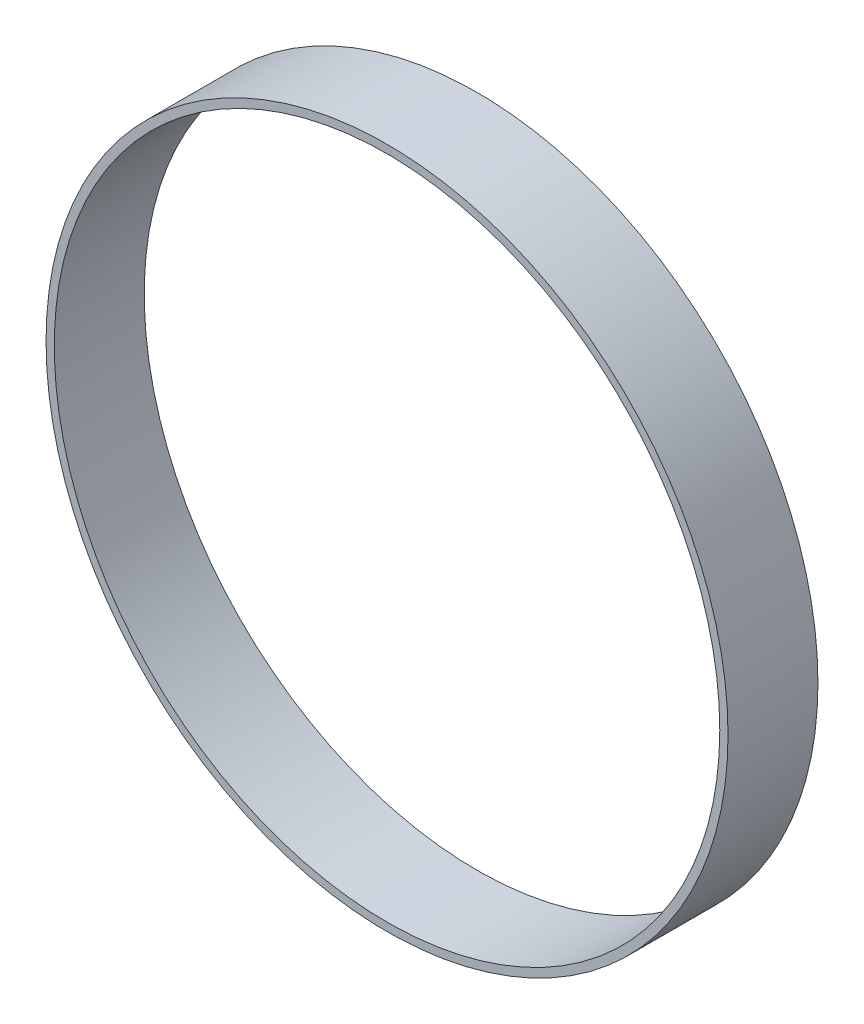
SolidWorks part; units mm, degrees
ref_plane "正面" through (0, 0, 0) normal (0, 0, 1) x (1, 0, 0)
ref_plane "平面" through (0, 0, 0) normal (0, 1, 0) x (1, 0, 0)
ref_plane "右側面" through (0, 0, 0) normal (1, 0, 0) x (0, 0, -1)
sketch "ｽｹｯﾁ1" plane through (0, 0, 0) normal (0, 0, 1) x (1, 0, 0)
  circle A0 centre (0, 0) radius 44.4
  circle A1 centre (0, 0) radius 45.5
  dimension "D1" = 88.8
  dimension "D2" = 91
extrude "ﾎﾞｽ - 押し出し1" add sketch "ｽｹｯﾁ1" along normal blind 12
